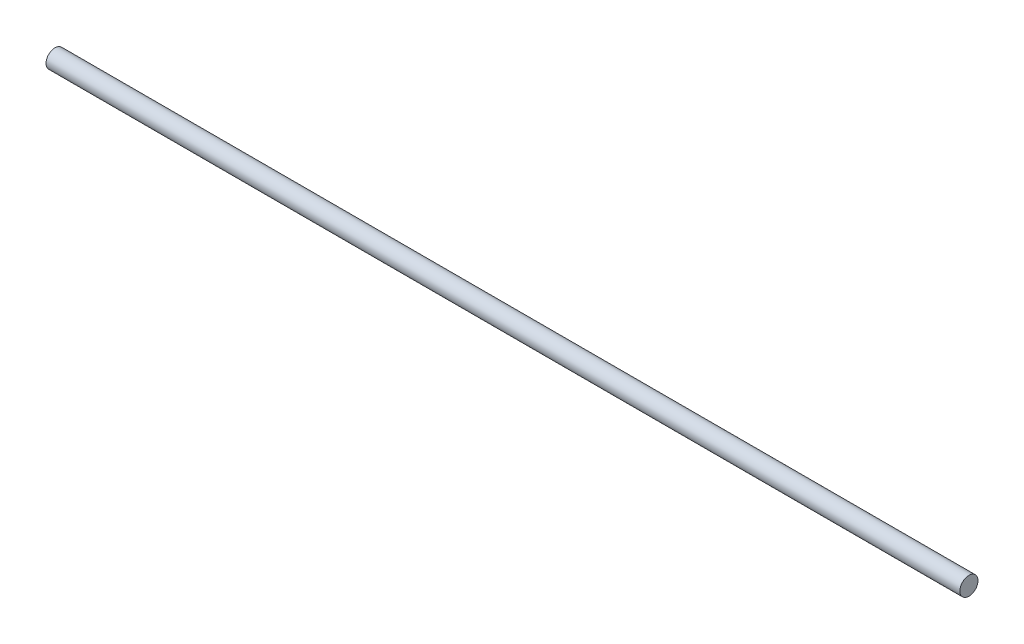
SolidWorks part; units mm, degrees
ref_plane "Front Plane" through (0, 0, 0) normal (0, 0, 1) x (1, 0, 0)
ref_plane "Top Plane" through (0, 0, 0) normal (0, 1, 0) x (1, 0, 0)
ref_plane "Right Plane" through (0, 0, 0) normal (1, 0, 0) x (0, 0, -1)
sketch "Sketch1" plane through (0, 0, 0) normal (1, 0, 0) x (0, 0, -1)
  circle A0 centre (0, 0) radius 7.9375
  dimension "D1" = 15.875
extrude "Boss-Extrude1" add sketch "Sketch1" along normal offset from surface (800 mm away) 10
